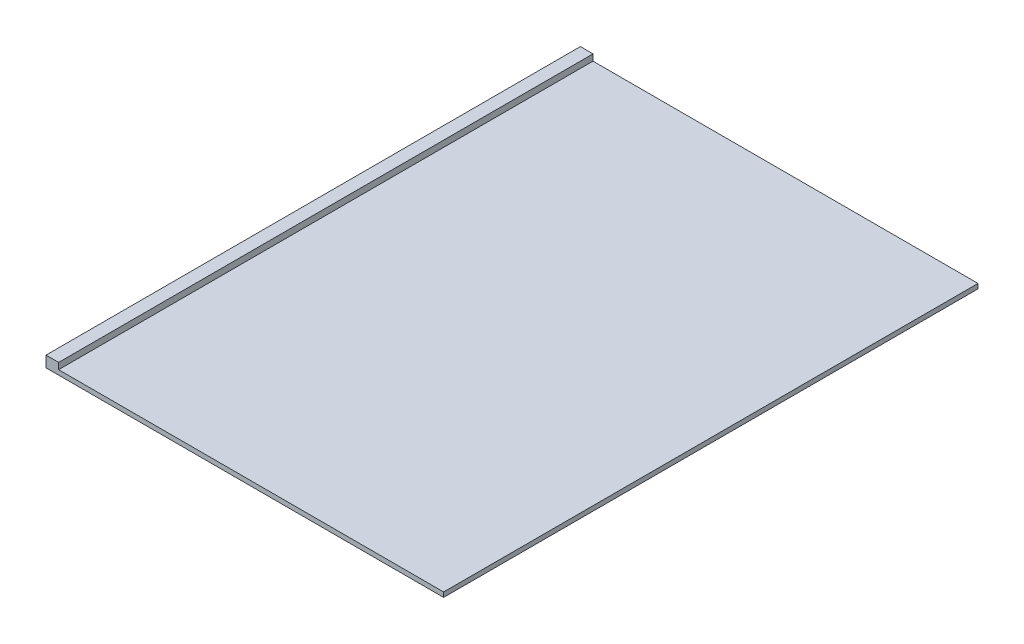
SolidWorks part; units mm, degrees
ref_plane "Piano frontale" through (0, 0, 0) normal (0, 0, 1) x (1, 0, 0)
ref_plane "Piano superiore" through (0, 0, 0) normal (0, 1, 0) x (1, 0, 0)
ref_plane "Piano destro" through (0, 0, 0) normal (1, 0, 0) x (0, 0, -1)
sketch "Schizzo1" plane through (0, 0, 0) normal (0, 1, 0) x (1, 0, 0)
  line L1 (0, 0) -> (94.5, 0)
  line L2 (0, 0) -> (0, 127)
  line L3 (0, 127) -> (94.5, 127)
  line L4 (94.5, 0) -> (94.5, 127)
  line L5 (0, 0) -> (94.5, 127) construction
  line L6 (0, 127) -> (94.5, 0) construction
  point P4 (47.25, 63.5)
  dimension "D1" = 127
  dimension "D2" = 94.5
extrude "Coperchio" add sketch "Schizzo1" along normal blind 1.125
sketch "Schizzo3" plane through (0, 1.125, 0) normal (0, 1, 0) x (1, 0, 0)
  line L0 (0, 127) -> (0, 0) construction
  line L1 (0, 127) -> (3, 127)
  line L2 (0, 127) -> (0, 0)
  line L3 (0, 0) -> (3, 0)
  line L4 (3, 127) -> (3, 0)
  line L5 (0, 127) -> (3, 0) construction
  line L6 (0, 0) -> (3, 127) construction
  line L7 (94.5, 127) -> (0, 127) construction
  line L8 (0, 0) -> (94.5, 0) construction
  point P4 (1.5, 63.5)
  dimension "D1" = 3
  dimension "D2" = 0
  dimension "D3" = 0
extrude "Incastro coperchio" add sketch "Schizzo3" along normal blind 1.5
